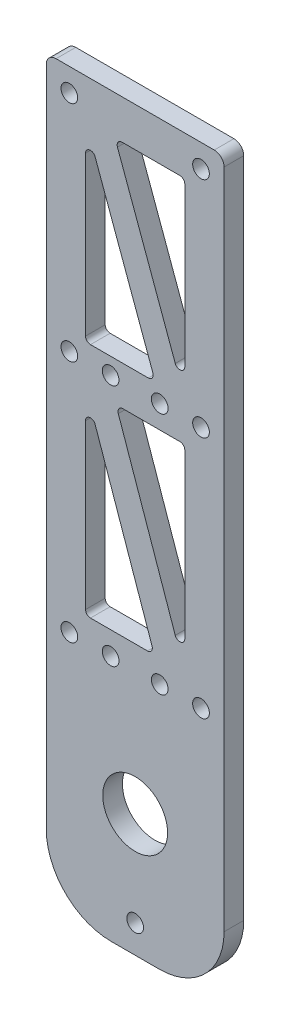
SolidWorks part; units mm, degrees
ref_plane "Front Plane" through (0, 0, 0) normal (0, 0, 1) x (1, 0, 0)
ref_plane "Top Plane" through (0, 0, 0) normal (0, 1, 0) x (1, 0, 0)
ref_plane "Right Plane" through (0, 0, 0) normal (1, 0, 0) x (0, 0, -1)
sketch "Sketch1" plane through (0, 0, 0) normal (0, 0, 1) x (1, 0, 0)
  line L0 (-10.1, 28.1) -> (4.1, 28.1)
  line L1 (-10.1, -20.1) -> (10.1, -20.1)
  line L2 (-10.1, -20.1) -> (-10.1, 20.1)
  line L3 (-10.1, 20.1) -> (10.1, 20.1)
  line L4 (10.1, -20.1) -> (10.1, 20.1)
  line L5 (-10.1, -20.1) -> (10.1, 20.1) construction
  line L6 (-10.1, 20.1) -> (10.1, -20.1) construction
  line L7 (-4.9, -75) -> (4.9, -75)
  line L8 (-18.1, -61.8) -> (-18.1, 75)
  line L9 (-18.1, 75) -> (18.1, 75)
  line L10 (18.1, -61.8) -> (18.1, 75)
  line L11 (-18.1, -75) -> (18.1, 75) construction
  line L12 (-18.1, 75) -> (18.1, -75) construction
  line L13 (4.1, 28.1) -> (-10.1, 67)
  line L14 (-10.1, 67) -> (-10.1, 28.1)
  line L17 (10.1, 67) -> (-4.1, 67)
  line L18 (-4.1, 67) -> (10.1, 28.1)
  line L19 (10.1, 28.1) -> (10.1, 67)
  circle A0 centre (0, -50.1) radius 6.6
  arc A1 (4.9, -75) -> (18.1, -61.8) centre (4.9, -61.8) ccw
  arc A2 (-4.9, -75) -> (-18.1, -61.8) centre (-4.9, -61.8) cw
  point P0 (0, 0)
  point P6 (0, 0)
  dimension "D4" = 13.2
  dimension "D6" = 13.2
  dimension "D1" = 40.2
  dimension "D2" = 20.2
  dimension "D3" = 150
  dimension "D5" = 30
  dimension "D7" = 8
  dimension "D8" = 8
  dimension "D9" = 8
  dimension "D10" = 8
  dimension "D11" = 8
  dimension "D12" = 8
  dimension "D13" = 14.2
  dimension "D14" = 14.2
extrude "Base Plate" add sketch "Sketch1" along normal blind 4
fillet "Fillet1" radius 1 6 edges at (-4.1, 67, 2) (10.1, 67, 2) (-10.1, 67, 2) (-10.1, 28.1, 2) (4.1, 28.1, 2) (10.1, 28.1, 2)
fillet "Fillet2" radius 2 2 edges at (-18.1, 75, 2) (18.1, 75, 2)
sketch "Sketch2" plane through (0, 0, 4) normal (0, 0, 1) x (1, 0, 0)
  line L0 (-4.9, -75) -> (4.9, -75) construction
  line L1 (2.2, 0) -> (-2.2, 0) construction
  line L2 (18.1, -61.8) -> (18.1, 73) construction
  line L3 (0, -2.2) -> (0, 2.2) construction
  line L4 (0, 75) -> (0, 67) construction
  line L5 (16.1, 75) -> (-16.1, 75) construction
  line L6 (9.1, 67) -> (-2.6704, 67) construction
  circle A0 centre (5, 24.75) radius 1.7
  circle A1 centre (-5, 24.75) radius 1.7
  circle A2 centre (-5, -24.75) radius 1.7
  circle A3 centre (5, -24.75) radius 1.7
  circle A4 centre (13.4, 24.75) radius 1.7
  circle A5 centre (-13.4, 24.75) radius 1.7
  circle A6 centre (13.4, -24.75) radius 1.7
  circle A7 centre (-13.4, -24.75) radius 1.7
  circle A9 centre (13.4, 70.3) radius 1.7
  circle A10 centre (-13.4, 70.3) radius 1.7
  circle A11 centre (0, -69.3) radius 1.7
  dimension "D1" = 3.4
  dimension "D2" = 3.4
  dimension "D6" = 3.4
  dimension "D8" = 3.4
  dimension "D7" = 3.4
  dimension "D3" = 10
  dimension "D4" = 5
  dimension "D5" = 49.5
  dimension "D9" = 4.7
  dimension "D10" = 4.7
  dimension "D11" = 5.7
extrude "Cut-Extrude1" cut sketch "Sketch2" against normal through all
sketch "Sketch3" plane through (10.1, 0, 0) normal (-1, 0, 0) x (0, 0, 1)
  line L4 (0, 20.1) -> (0, -20.1)
  line L5 (0, -20.1) -> (4, -20.1)
  line L6 (4, -20.1) -> (4, 20.1)
  line L7 (4, 20.1) -> (0, 20.1)
  line L8 (0, 20.1) -> (0, -20.1)
  line L9 (0, -20.1) -> (4, -20.1)
  line L10 (4, -20.1) -> (4, 20.1)
  line L11 (4, 20.1) -> (0, 20.1)
  dimension "D1" = 0
extrude "Boss-Extrude1" add sketch "Sketch3" along direction (1, 0, 0) on the side of the normal through all
sketch "Sketch4" plane through (0, 0, 4) normal (0, 0, 1) x (1, 0, 0)
  line L0 (-10.1, 20.1) -> (-10.1, -20.1)
  line L1 (-10.1, -20.1) -> (3.9, -20.1)
  line L2 (3.9, -20.1) -> (-10.1, 20.1)
  line L3 (-3.9, 20.1) -> (10.1, 20.1)
  line L4 (10.1, 20.1) -> (10.1, -20.1)
  line L5 (10.1, -20.1) -> (-3.9, 20.1)
  line L6 (-10.1, 61.3443) -> (-10.1, 29.1) construction
  line L7 (10.1, 33.7557) -> (10.1, 66) construction
  point P13 (10.1, 0)
  dimension "D1" = 14
  dimension "D2" = 14
  dimension "D3" = 40.2
extrude "Cut-Extrude2" cut sketch "Sketch4" against normal through all
fillet "Fillet3" radius 1 6 edges at (10.1, -20.1, 2) (10.1, 20.1, 2) (-3.9, 20.1, 2) (-10.1, 20.1, 2) (3.9, -20.1, 2) (-10.1, -20.1, 2)
equation "\"D8@Sketch1\"=\"D9@Sketch1\""
equation "\"D10@Sketch1\"=\"D9@Sketch1\""
equation "\"D11@Sketch1\"=\"D9@Sketch1\""
equation "\"D12@Sketch1\"=\"D9@Sketch1\""
equation "\"D13@Sketch1\"=\"D2@Sketch1\"-6"
equation "\"D14@Sketch1\"=\"D13@Sketch1\""
equation "\"D6@Sketch1\"=\"D4@Sketch1\""
equation "\"D2@Sketch2\"=\"D1@Sketch2\""
equation "\"D4@Sketch2\"=\"D3@Sketch2\"/2"
equation "\"D9@Sketch2\"=3+(\"D8@Sketch2\"/2)"
equation "\"D10@Sketch2\"=\"D9@Sketch2\""
equation "\"D11@Sketch2\"=\"D7@Sketch2\"/2+4"
